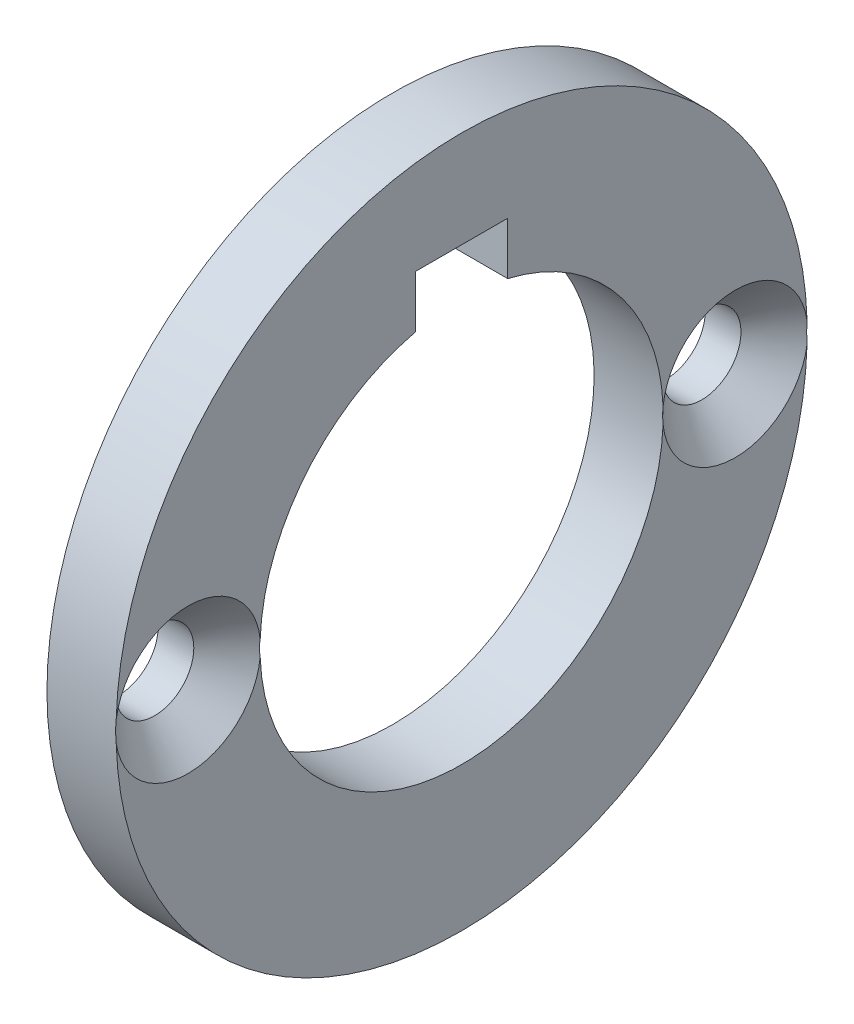
SolidWorks part; units mm, degrees
ref_plane "Plane1" through (0, 0, 0) normal (0, 0, 1) x (1, 0, 0)
ref_plane "Plane2" through (0, 0, 0) normal (0, 1, 0) x (1, 0, 0)
ref_plane "Plane3" through (0, 0, 0) normal (1, 0, 0) x (0, 0, -1)
sketch "Sketch1" plane through (0, 0, 0) normal (0, 0, 1) x (1, 0, 0)
  line L0 (-34.925, 0) -> (9.525, 0) construction
  line L1 (0, 8.75) -> (0, 15)
  line L2 (0, 15) -> (-3, 15)
  line L3 (-3, 15) -> (-3, 8.75)
  line L4 (-3, 8.75) -> (0, 8.75)
  dimension "Thickness" = 3
  dimension "Inside_dia" = 17.5
  dimension "Outside_dia" = 30
revolve "Base-Revolve" add sketch "Sketch1" angle 360 about L0
sketch "Sketch2" plane through (0, 0, 0) normal (1, 0, 0) x (0, 0, -1)
  line L0 (-2, 10.7899) -> (-2, 6.7899)
  line L1 (-2, 10.7899) -> (2, 10.7899)
  line L2 (-2, 6.7899) -> (2, 6.7899)
  line L3 (2, 10.7899) -> (2, 6.7899)
  line L4 (-2, 10.7899) -> (2, 6.7899) construction
  line L5 (-2, 6.7899) -> (2, 10.7899) construction
  line L6 (0, 0) -> (0, 8.7899) construction
  circle A0 centre (0, 1.2899) radius 7.5 construction
  circle A1 centre (0, 0) radius 8.75 construction
  circle A2 centre (-11.875, 0) radius 1.5
  circle A3 centre (-11.875, 0) radius 3.125 construction
  circle A4 centre (0, 0) radius 15 construction
  circle A5 centre (11.875, 0) radius 1.5
  point P3 (0, 8.7899)
  point P5 (2, 8.5184)
  point P11 (-2, 8.7899)
  point P12 (-2, 8.5184)
  dimension "D2" = 15
  dimension "D3" = 3
  dimension "D1" = 4
extrude "Cut-Extrude1" cut sketch "Sketch2" against normal blind 10
hole_wizard "CSK for M3 Countersunk Flat Head Screw1" positions "Sketch4" profile "Sketch3" countersink size "M3" standard "ISO"
sketch "Sketch4" plane through (0, 0, 0) normal (1, 0, 0) x (0, 0, -1)
  point P0 (-11.875, 0)
  point P4 (11.875, 0)
sketch "Sketch3" plane through (0, 0, 11.875) normal (0, 1, 0) x (0, 0, -1)
  line L0 (0, 0) -> (0, 21.0245)
  line L1 (0, 21.0245) -> (1.7, 20.003)
  line L2 (1.7, 20.003) -> (1.7, 1.45)
  line L3 (1.7, 1.45) -> (3.15, 0)
  line L5 (3.15, 0) -> (0, 0)
  line L6 (-1.7, 1.45) -> (-3.15, 0) construction
  line L10 (0, 21.0245) -> (-1.7, 20.003) construction
  line L11 (0, -6.35) -> (0, 107.95) construction
  dimension "Hole Dia." = 3.4
  dimension "Hole Depth" = 20.003
  dimension "Near C'Sink Dia." = 6.3
  dimension "Near C'Sink Angle" = 90
  dimension "Drill Angle" = 118
